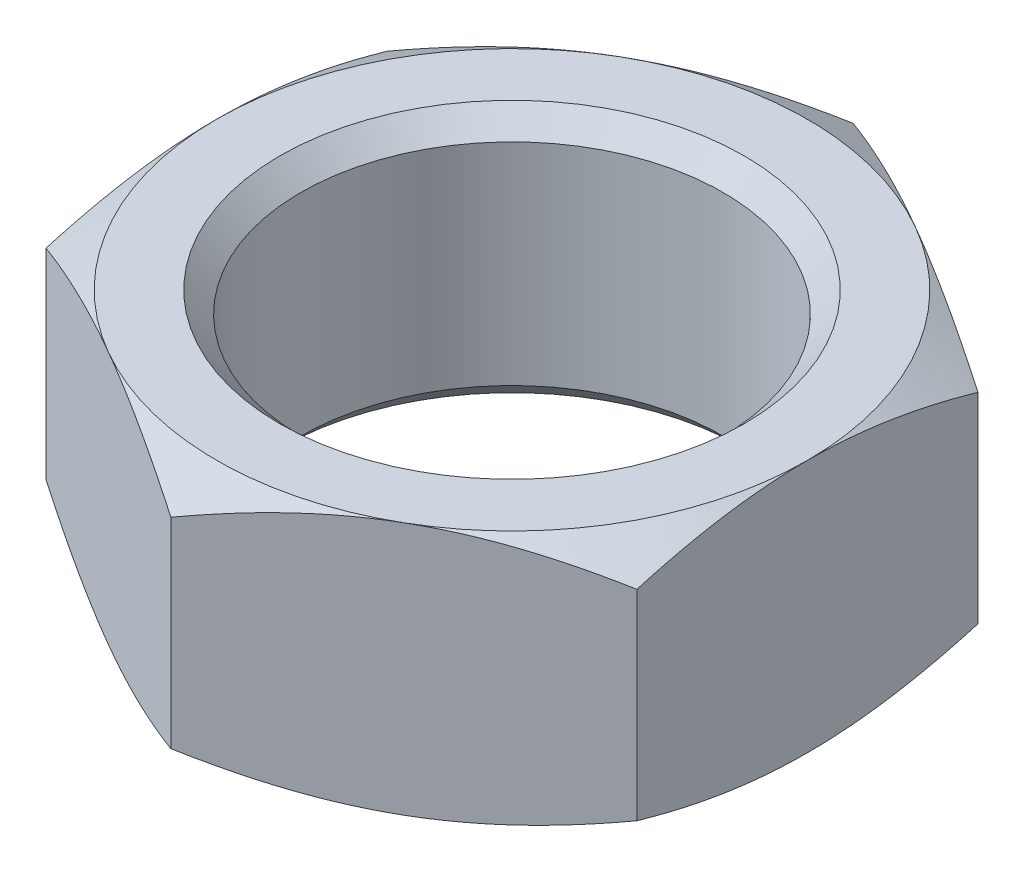
SolidWorks part; units mm, degrees
material "AISI 1020"
ref_plane "Front Plane" through (0, 0, 0) normal (0, 0, 1) x (1, 0, 0)
ref_plane "Top Plane" through (0, 0, 0) normal (0, 1, 0) x (1, 0, 0)
ref_plane "Right Plane" through (0, 0, 0) normal (1, 0, 0) x (0, 0, -1)
sketch "Sketch1" plane through (0, 0, 0) normal (0, 1, 0) x (1, 0, 0)
  line L1 (14, 8.0829) -> (0, 16.1658)
  line L2 (0, 16.1658) -> (-14, 8.0829)
  line L3 (-14, 8.0829) -> (-14, -8.0829)
  line L4 (-14, -8.0829) -> (0, -16.1658)
  line L5 (0, -16.1658) -> (14, -8.0829)
  line L6 (14, -8.0829) -> (14, 8.0829)
  circle A0 centre (0, 0) radius 14 construction
  dimension "D1" = 28
extrude "Boss-Extrude1" add sketch "Sketch1" along normal mid plane 12
sketch "Sketch2" plane through (0, 6, 0) normal (0, 1, 0) x (1, 0, 0)
  line L0 (14, 8.0829) -> (0, 16.1658) construction
  circle A0 centre (0, 0) radius 14
extrude "Cut-Extrude1" cut sketch "Sketch2" against normal blind 12 draft 60 flip side to cut
mirror "Mirror1" about plane through (0, 0, 0) normal (0, 1, 0) of "Cut-Extrude1"
sketch "Sketch3" plane through (0, 6, 0) normal (0, 1, 0) x (1, 0, 0)
  circle A0 centre (0, 0) radius 10
  dimension "D1" = 20
extrude "Cut-Extrude2" cut sketch "Sketch3" against normal through all
chamfer "Chamfer1" distance 1 angle 45 2 edges at (0, -6, 10) (0, 6, 10)
